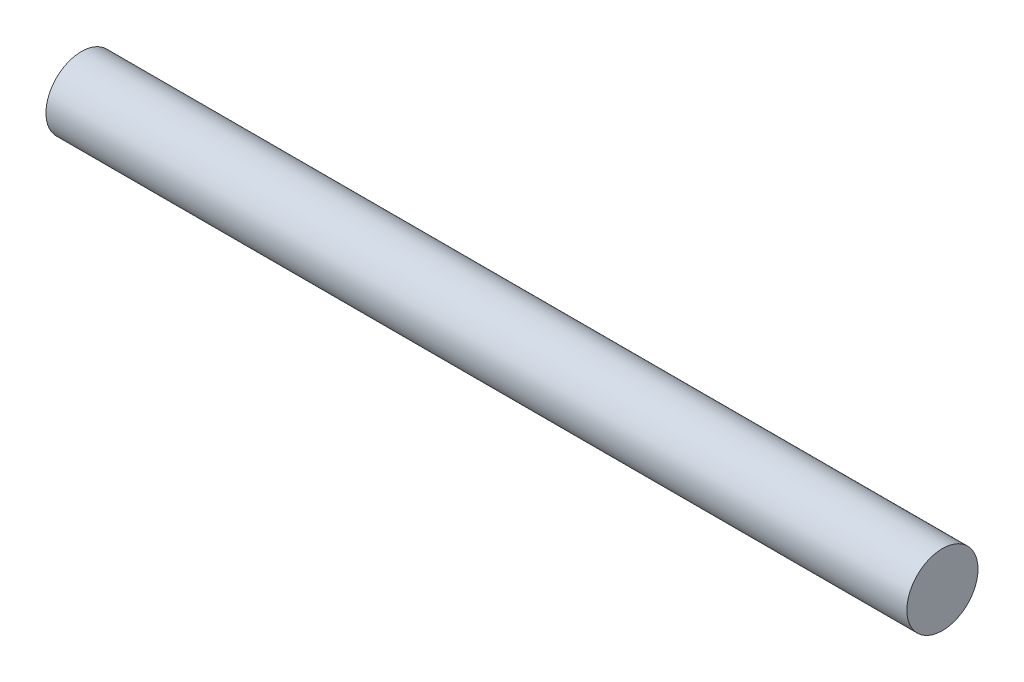
SolidWorks part; units mm, degrees
ref_plane "前视基准面" through (0, 0, 0) normal (0, 0, 1) x (1, 0, 0)
ref_plane "上视基准面" through (0, 0, 0) normal (0, 1, 0) x (1, 0, 0)
ref_plane "右视基准面" through (0, 0, 0) normal (1, 0, 0) x (0, 0, -1)
sketch "草图1" plane through (0, 0, 0) normal (1, 0, 0) x (0, 0, -1)
  circle A0 centre (0, 0) radius 3
extrude "凸台-拉伸1" add sketch "草图1" along normal blind 72.63
